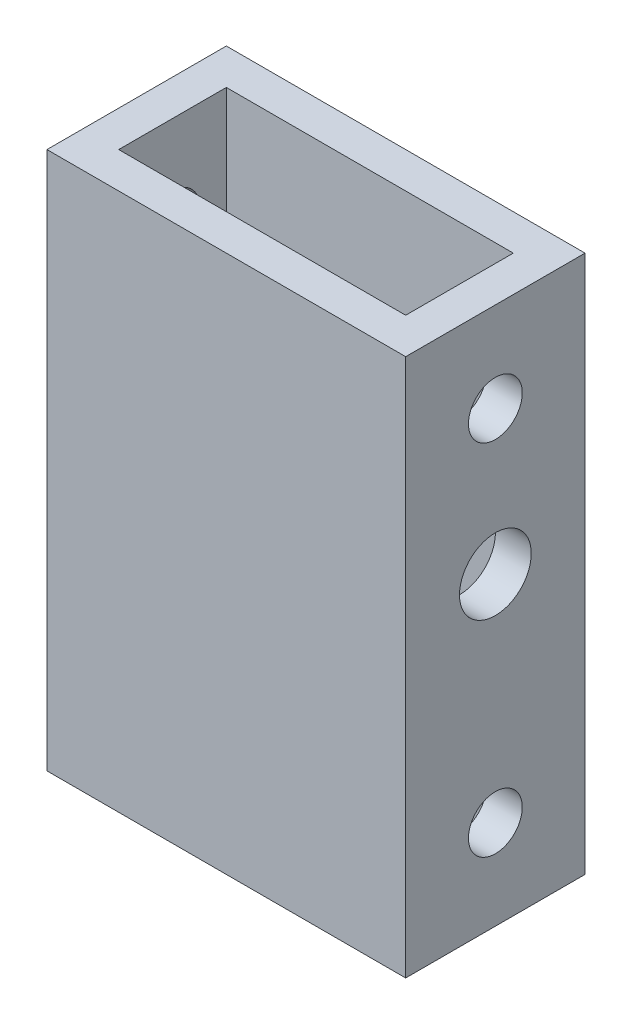
SolidWorks part; units mm, degrees
ref_plane "前视基准面" through (0, 0, 0) normal (0, 0, 1) x (1, 0, 0)
ref_plane "上视基准面" through (0, 0, 0) normal (0, 1, 0) x (1, 0, 0)
ref_plane "右视基准面" through (0, 0, 0) normal (1, 0, 0) x (0, 0, -1)
sketch "草图1" plane through (0, 0, 0) normal (0, 1, 0) x (1, 0, 0)
  line L1 (-10, 5) -> (10, 5)
  line L2 (-10, 5) -> (-10, -5)
  line L3 (-10, -5) -> (10, -5)
  line L4 (10, 5) -> (10, -5)
  line L5 (-10, 5) -> (10, -5) construction
  line L6 (-10, -5) -> (10, 5) construction
  line L7 (-8, 3) -> (8, 3)
  line L8 (-8, 3) -> (-8, -3)
  line L9 (-8, -3) -> (8, -3)
  line L10 (8, 3) -> (8, -3)
  line L11 (-8, 3) -> (8, -3) construction
  line L12 (-8, -3) -> (8, 3) construction
  point P0 (0, 0)
  point P6 (0, 0)
  dimension "D1" = 20
  dimension "D2" = 10
  dimension "D3" = 2
  dimension "D4" = 2
extrude "凸台-拉伸1" add sketch "草图1" along normal mid plane 30
sketch "草图2" plane through (-10, 0, 0) normal (-1, 0, 0) x (0, 0, 1)
  line L0 (0, 10) -> (0, -10) construction
  line L1 (-5, 15) -> (5, 15) construction
  line L2 (-5, -15) -> (5, -15) construction
  circle A0 centre (0, 2) radius 2
  circle A1 centre (0, 10) radius 1.5
  circle A2 centre (0, -10) radius 1.5
  dimension "D1" = 4
  dimension "D4" = 3
  dimension "D2" = 5
  dimension "D3" = 5
extrude "切除-拉伸1" cut sketch "草图2" against normal through all
